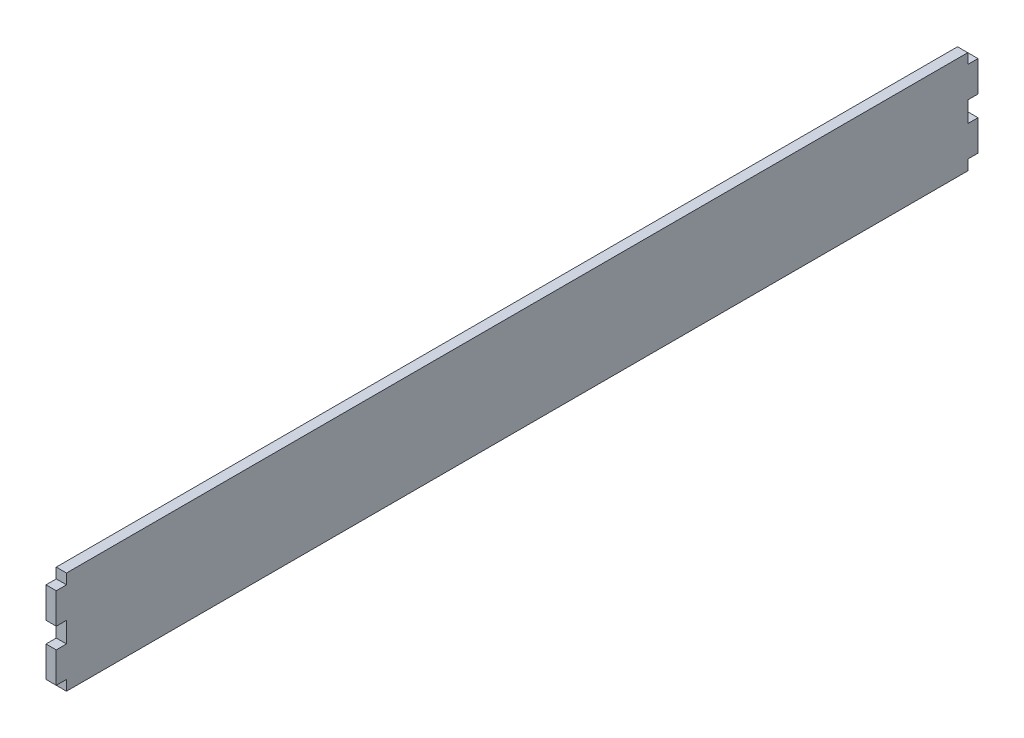
SolidWorks part; units mm, degrees
ref_plane "Front Plane" through (0, 0, 0) normal (0, 0, 1) x (1, 0, 0)
ref_plane "Top Plane" through (0, 0, 0) normal (0, 1, 0) x (1, 0, 0)
ref_plane "Right Plane" through (0, 0, 0) normal (1, 0, 0) x (0, 0, -1)
sketch "Sketch1" plane through (0, 0, 0) normal (1, 0, 0) x (0, 0, -1)
  line L0 (225, -5) -> (225, -20)
  line L1 (-220, 25) -> (220, 25)
  line L2 (-220, 25) -> (-220, 20)
  line L3 (-220, -25) -> (220, -25)
  line L4 (220, 25) -> (220, 20)
  line L5 (-220, 25) -> (220, -25) construction
  line L6 (-220, -25) -> (220, 25) construction
  line L7 (220, 20) -> (225, 20)
  line L9 (220, 5) -> (225, 5)
  line L10 (225, 20) -> (225, 5)
  line L11 (220, -5) -> (225, -5)
  line L12 (220, -20) -> (225, -20)
  line L13 (0, 25) -> (0, 33.557) construction
  line L14 (-220, -20) -> (-225, -20)
  line L15 (-220, -5) -> (-225, -5)
  line L16 (-225, 20) -> (-225, 5)
  line L17 (-220, 5) -> (-225, 5)
  line L19 (-220, 20) -> (-225, 20)
  line L20 (-225, -5) -> (-225, -20)
  line L21 (-220, -20) -> (-220, -25)
  line L22 (-220, 5) -> (-220, -5)
  line L23 (220, 5) -> (220, -5)
  line L24 (220, -20) -> (220, -25)
  point P0 (0, 0)
  dimension "D1" = 50
  dimension "D2" = 440
  dimension "D3" = 5
  dimension "D4" = 15
  dimension "D5" = 5
  dimension "D6" = 2
extrude "Boss-Extrude1" add sketch "Sketch1" along normal blind 5
